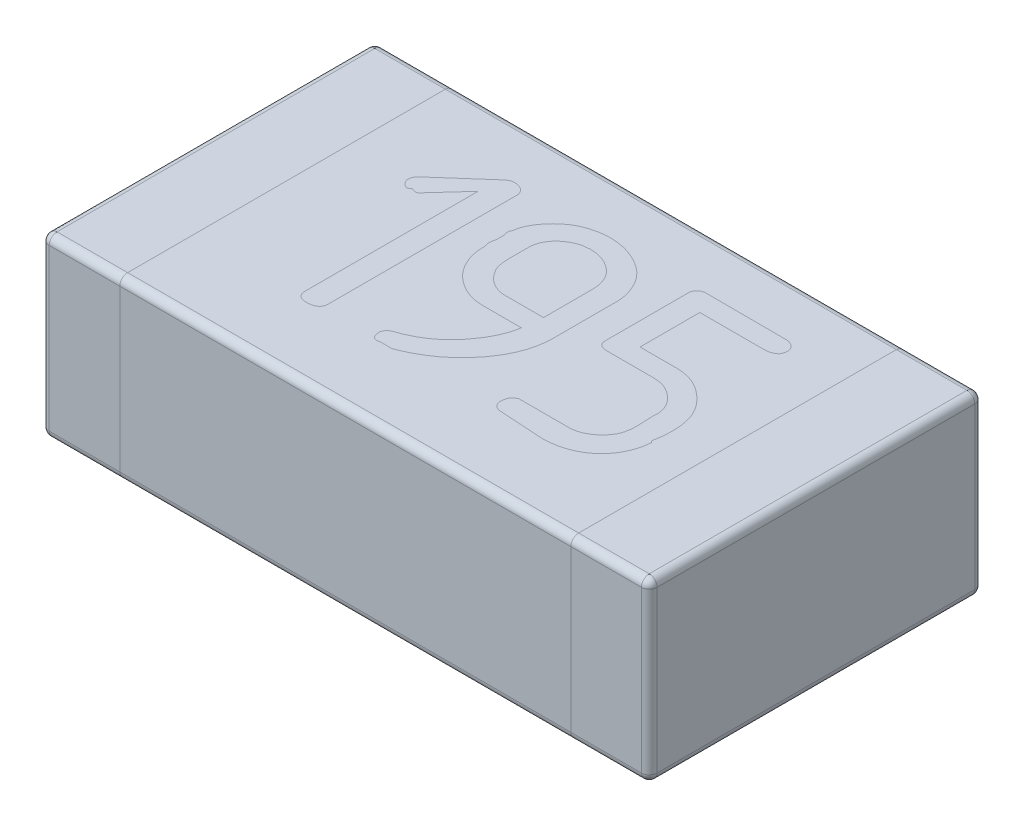
SolidWorks part; units mm, degrees
ref_plane "Front Plane" through (0, 0, 0) normal (0, 0, 1) x (1, 0, 0)
ref_plane "Top Plane" through (0, 0, 0) normal (0, 1, 0) x (1, 0, 0)
ref_plane "Right Plane" through (0, 0, 0) normal (1, 0, 0) x (0, 0, -1)
sketch "Sketch1" plane through (0, 0, 0) normal (0, 1, 0) x (1, 0, 0)
  line L1 (-0.755, -0.425) -> (0.755, -0.425)
  line L2 (-0.775, -0.405) -> (-0.775, 0.405)
  line L3 (-0.755, 0.425) -> (0.755, 0.425)
  line L4 (0.775, -0.405) -> (0.775, 0.405)
  line L5 (-0.775, -0.425) -> (0.775, 0.425) construction
  line L6 (-0.775, 0.425) -> (0.775, -0.425) construction
  arc A4 (-0.775, -0.405) -> (-0.755, -0.425) centre (-0.755, -0.405) ccw
  arc A5 (0.755, -0.425) -> (0.775, -0.405) centre (0.755, -0.405) ccw
  arc A6 (0.775, 0.405) -> (0.755, 0.425) centre (0.755, 0.405) ccw
  arc A7 (-0.755, 0.425) -> (-0.775, 0.405) centre (-0.755, 0.405) ccw
  point P0 (0, 0)
  dimension "D4" = 0.02
  dimension "D1" = 1.55
  dimension "D2" = 0.85
extrude "Boss-Extrude1" add sketch "Sketch1" along normal mid plane 0.45
sketch "Sketch3" plane through (0, 0.225, 0) normal (0, 1, 0) x (1, 0, 0)
  line L0 (-0.575, 0) -> (0.575, 0) construction
  line L1 (-0.575, -0.5133) -> (-0.575, 0.5133)
  line L2 (0.575, -0.5133) -> (0.575, 0.5133)
  line L3 (0, -0.25) -> (0, 0.25) construction
  line L6 (-0.575, -0.25) -> (0.575, -0.25) construction
  text T0 "<b>195</b>\r\n" font "SWIsop1" height 0.53
  point P4 (0, 0)
  point P8 (-0.575, 0)
  point P11 (0.575, 0)
  point P14 (0, 0)
  point P17 (0, -0.25)
  dimension "D1" = 1.15
  dimension "D2" = 0.5
sketch "Sketch4" plane through (0, 0, 0.425) normal (0, 0, 1) x (1, 0, 0)
  line L0 (-0.575, 0.225) -> (-0.575, -0.5946)
  line L1 (0.575, 0.225) -> (0.575, -0.5946)
sketch "Sketch5" plane through (0, 0, -0.425) normal (0, 0, -1) x (-1, 0, 0)
  line L0 (-0.575, 0.225) -> (-0.575, -0.5946) construction
  line L1 (-0.575, 0.225) -> (-0.575, -0.5946)
  line L2 (0.575, 0.225) -> (0.575, -0.5946) construction
  line L3 (0.575, 0.225) -> (0.575, -0.5946)
sketch "Sketch6" plane through (0, -0.225, 0) normal (0, -1, 0) x (1, 0, 0)
  line L0 (0.575, 0.5133) -> (0.575, -0.5133) construction
  line L1 (-0.575, 0.5133) -> (-0.575, -0.5133) construction
  line L2 (0.575, 0.5133) -> (0.575, -0.5133)
  line L3 (-0.575, 0.5133) -> (-0.575, -0.5133)
split line "Split Line2"
split line "Split Line3"
split line "Split Line4"
split line "Split Line5"
fillet "Fillet2" radius 0.02 24 edges at (-0.665, -0.225, 0.425) (0, -0.225, 0.425) (0.665, -0.225, 0.425) (-0.7691, -0.225, 0.4191) (-0.775, -0.225, 0) (-0.7691, -0.225, -0.4191) (0.665, -0.225, -0.425) (0, -0.225, -0.425) (-0.665, -0.225, -0.425) (0.7691, -0.225, -0.4191) (0.775, -0.225, 0) (0.7691, -0.225, 0.4191) (-0.7691, 0.225, 0.4191) (-0.775, 0.225, 0) (-0.7691, 0.225, -0.4191) (0.665, 0.225, -0.425) (0, 0.225, -0.425) (-0.665, 0.225, -0.425) (0.7691, 0.225, -0.4191) (0.775, 0.225, 0) (0.7691, 0.225, 0.4191) (-0.665, 0.225, 0.425) (0, 0.225, 0.425) (0.665, 0.225, 0.425)
